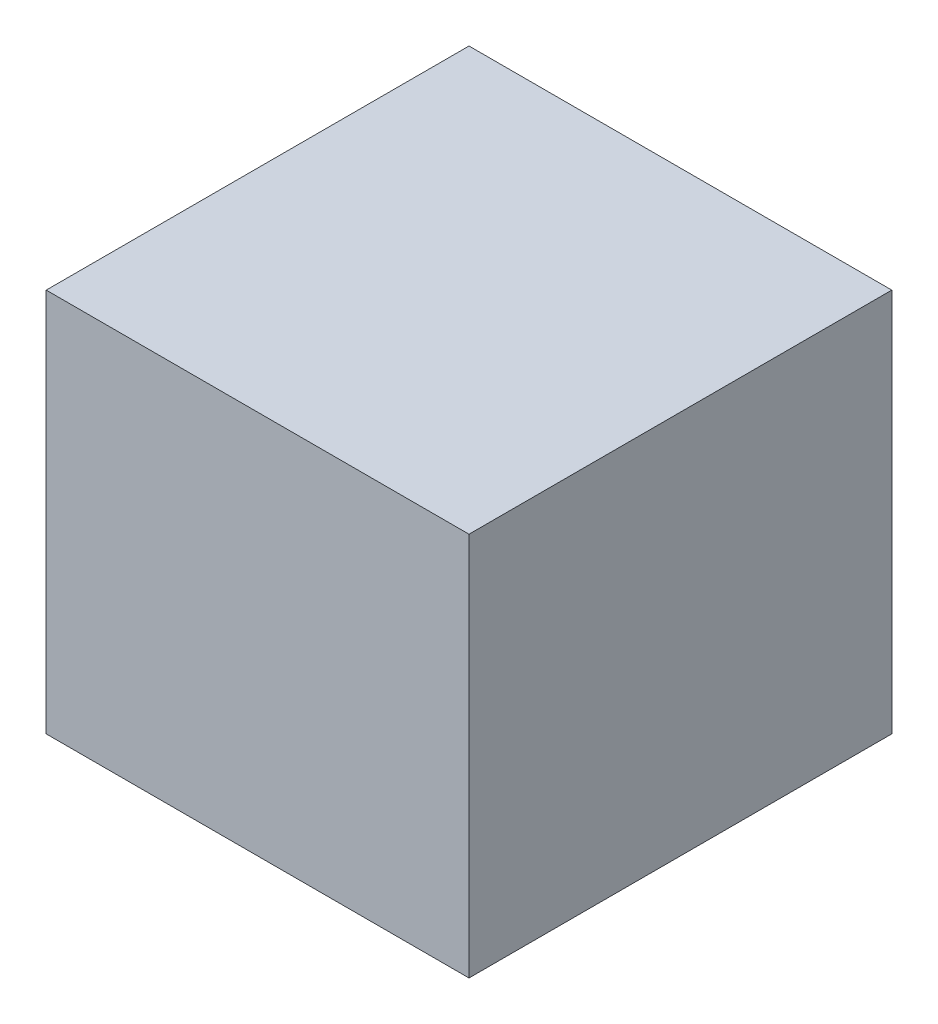
SolidWorks part; units mm, degrees
ref_plane "Front Plane" through (0, 0, 0) normal (0, 0, 1) x (1, 0, 0)
ref_plane "Top Plane" through (0, 0, 0) normal (0, 1, 0) x (1, 0, 0)
ref_plane "Right Plane" through (0, 0, 0) normal (1, 0, 0) x (0, 0, -1)
sketch "Sketch1" plane through (0, 0, 0) normal (0, 1, 0) x (1, 0, 0)
  line L1 (139.7, -139.7) -> (-139.7, -139.7)
  line L2 (139.7, -139.7) -> (139.7, 139.7)
  line L3 (139.7, 139.7) -> (-139.7, 139.7)
  line L4 (-139.7, -139.7) -> (-139.7, 139.7)
  line L5 (139.7, -139.7) -> (-139.7, 139.7) construction
  line L6 (139.7, 139.7) -> (-139.7, -139.7) construction
  point P0 (0, 0)
  dimension "D1" = 279.4
  dimension "D2" = 279.4
extrude "Boss-Extrude1" add sketch "Sketch1" along normal blind 254
